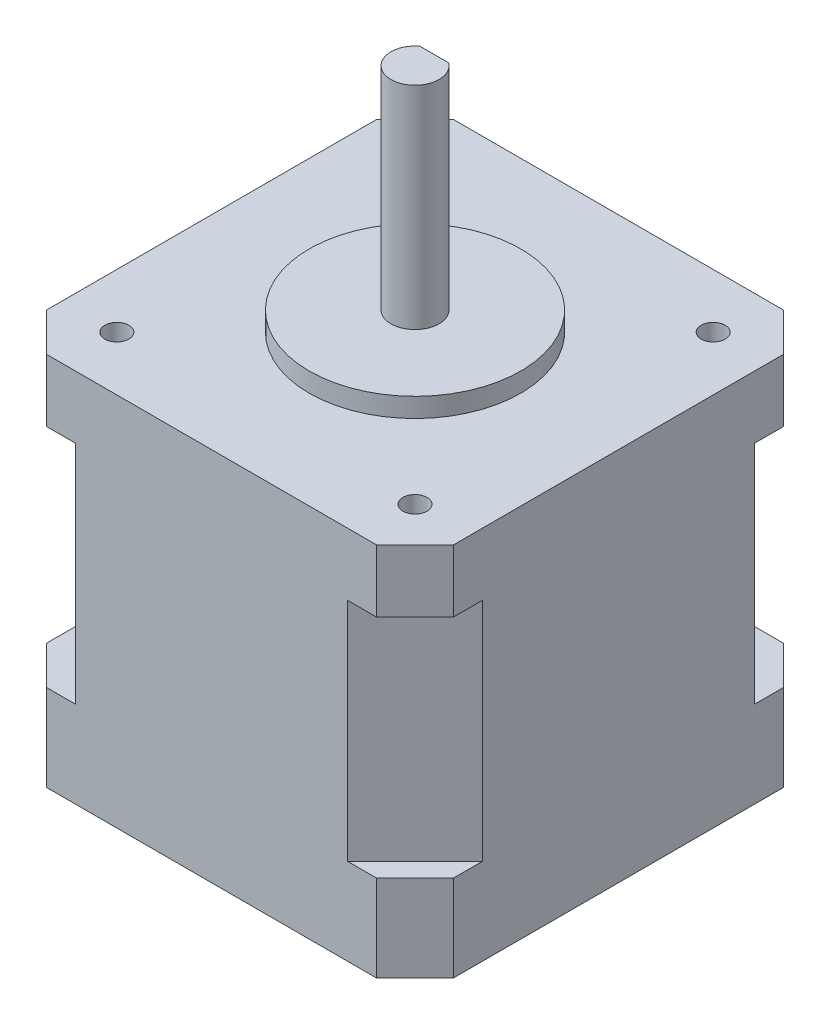
SolidWorks part; units mm, degrees
ref_plane "Plan de face" through (0, 0, 0) normal (0, 0, 1) x (1, 0, 0)
ref_plane "Plan de dessus" through (0, 0, 0) normal (0, 1, 0) x (1, 0, 0)
ref_plane "Plan de droite" through (0, 0, 0) normal (1, 0, 0) x (0, 0, -1)
sketch "Esquisse1" plane through (0, 0, 0) normal (0, 1, 0) x (1, 0, 0)
  line L1 (-21.15, 21.15) -> (21.15, 21.15)
  line L2 (-21.15, 21.15) -> (-21.15, -21.15)
  line L3 (-21.15, -21.15) -> (21.15, -21.15)
  line L4 (21.15, 21.15) -> (21.15, -21.15)
  point P4 (0, 21.15)
  point P6 (-21.15, 0)
  dimension "D1" = 42.3
extrude "Boss.-Extru.1" add sketch "Esquisse1" along normal blind 39
sketch "Esquisse2" plane through (0, 39, 0) normal (0, 1, 0) x (1, 0, 0)
  circle A0 centre (0, 0) radius 11
  dimension "D1" = 22
extrude "Boss.-Extru.2" add sketch "Esquisse2" along normal blind 2
sketch "Esquisse3" plane through (0, 41, 0) normal (0, 1, 0) x (1, 0, 0)
  line L0 (-1.5, 2) -> (1.5, 2)
  arc A1 (-1.5, 2) -> (1.5, 2) centre (0, 0) ccw
  point P6 (0, -2.5)
  dimension "D1" = 2.5
  dimension "D2" = 4.5
extrude "Boss.-Extru.3" add sketch "Esquisse3" along normal blind 22
hole_wizard "Trou pour taraudage pour trou taraudé M31" positions "Esquisse7" profile "Esquisse6" hole size "M3" standard "DIN"
sketch "Esquisse7" plane through (0, 39, 0) normal (0, 1, 0) x (1, 0, 0)
  line L0 (0, 0) -> (0, 4.5387) construction
  line L2 (0, 0) -> (4.1956, 0) construction
  point P0 (-15.5, 15.5)
  point P12 (15.5, 15.5)
  point P13 (15.5, -15.5)
  point P14 (-15.5, -15.5)
  dimension "D1" = 31
  dimension "D2" = 31
sketch "Esquisse6" plane through (-15.5, 39, -15.5) normal (1, 0, 0) x (0, 0, 1)
  line L0 (0, 0) -> (0, 4.8)
  line L1 (0, 4.8) -> (1.25, 4.0489)
  line L2 (1.25, 4.0489) -> (1.25, 0)
  line L5 (1.25, 0) -> (0, 0)
  line L10 (0, 4.8) -> (-1.25, 4.0489) construction
  line L11 (0, -6.35) -> (0, 107.95) construction
  dimension "Diamètre du perçage" = 2.5
  dimension "Profondeur du perçage" = 4.8
  dimension "Angle de pointe" = 118
chamfer "Chanfrein1" distance 4 angle 45 4 edges at (-21.15, 19.5, -21.15) (21.15, 19.5, -21.15) (21.15, 19.5, 21.15) (-21.15, 19.5, 21.15)
sketch "Esquisse4" plane through (0, 0, 0) normal (0, 1, 0) x (1, 0, 0)
  line L0 (0, 0) -> (0, 5.1071) construction
  line L1 (0, 0) -> (5.8035, 0) construction
  line L2 (-14.15, 21.15) -> (-21.15, 14.15)
  line L3 (17.15, 21.15) -> (-17.15, 21.15) construction
  line L4 (-21.15, 17.15) -> (-21.15, -17.15) construction
  line L5 (-21.15, 14.15) -> (-21.15, 21.15)
  line L6 (-21.15, 21.15) -> (-14.15, 21.15)
  line L7 (21.15, 21.15) -> (14.15, 21.15)
  line L8 (21.15, 14.15) -> (21.15, 21.15)
  line L9 (14.15, 21.15) -> (21.15, 14.15)
  line L10 (14.15, -21.15) -> (21.15, -14.15)
  line L11 (21.15, -14.15) -> (21.15, -21.15)
  line L12 (21.15, -21.15) -> (14.15, -21.15)
  line L13 (-21.15, -21.15) -> (-14.15, -21.15)
  line L14 (-21.15, -14.15) -> (-21.15, -21.15)
  line L15 (-14.15, -21.15) -> (-21.15, -14.15)
  dimension "D1" = 7
extrude "Enlèv. mat.-Extru.1" cut sketch "Esquisse4" along normal blind 23.5 from offset 9
sketch "Esquisse5" plane through (-21.15, 0, 0) normal (-1, 0, 0) x (0, 0, 1)
  line L0 (0, 0) -> (0, 2.0466) construction
  line L1 (-17.15, 0) -> (17.15, 0) construction
  circle A0 centre (-1, 7) radius 0.7
  circle A1 centre (-1, 5) radius 0.6547
  circle A2 centre (1, 5) radius 0.6547
  circle A3 centre (1, 7) radius 0.7
  dimension "D2" = 1.4
  dimension "D1" = 2
  dimension "D3" = 2
  dimension "D4" = 5
extrude "Boss.-Extru.4" add sketch "Esquisse5" along normal blind 10
equation "\"D3@Esquisse5\"=\"D1@Esquisse5\""
equation "\"D2@Esquisse7\"=\"D1@Esquisse7\""
